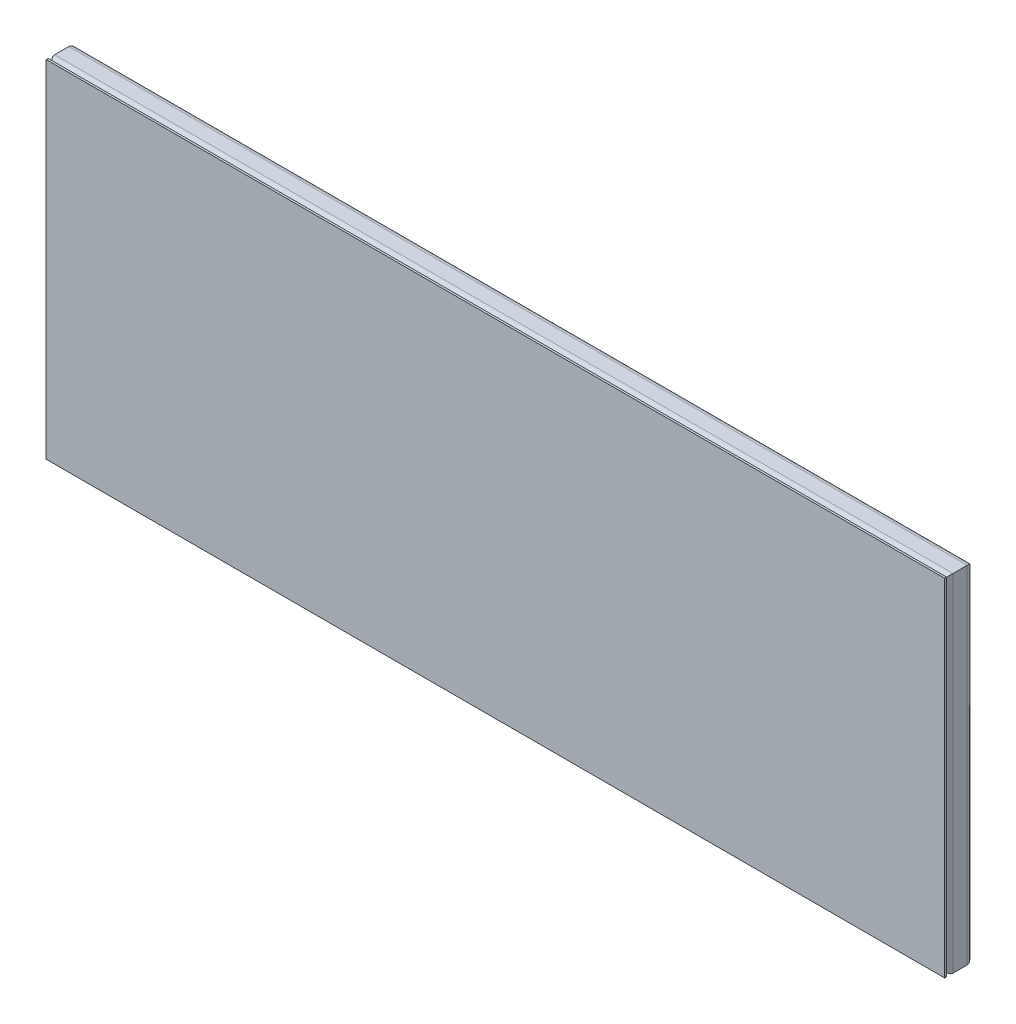
SolidWorks part; units mm, degrees
ref_plane "Alzado" through (0, 0, 0) normal (0, 0, 1) x (1, 0, 0)
ref_plane "Planta" through (0, 0, 0) normal (0, 1, 0) x (1, 0, 0)
ref_plane "Vista lateral" through (0, 0, 0) normal (1, 0, 0) x (0, 0, -1)
sketch "Croquis1" plane through (0, 0, 0) normal (0, 0, 1) x (1, 0, 0)
  line L1 (-400, 138.5) -> (400, 138.5)
  line L2 (-400, 138.5) -> (-400, -138.5)
  line L3 (-400, -138.5) -> (400, -138.5)
  line L4 (400, 138.5) -> (400, -138.5)
  line L5 (-400, 138.5) -> (400, -138.5) construction
  line L6 (-400, -138.5) -> (400, 138.5) construction
  point P0 (0, 0)
  dimension "D1" = 800
  dimension "D2" = 277
other "Tubo cuadrado 2 X 2 X 0.25(1)"
ref_plane "Plano1" through (-412.7, 138.5, 12.7) normal (0, -1, 0) x (1, 0, 0)
sketch "Sketch1" plane through (-412.7, 138.5, 12.7) normal (0, -1, 0) x (1, 0, 0)
  line L0 (-6.7, -9.7) -> (6.7, -9.7)
  line L1 (-9.7, -6.7) -> (-9.7, 6.7)
  line L2 (6.7, 9.7) -> (-6.7, 9.7)
  line L3 (9.7, 6.7) -> (9.7, -6.7)
  line L4 (-6.7, -12.7) -> (6.7, -12.7)
  line L5 (-12.7, -6.7) -> (-12.7, 6.7)
  line L6 (6.7, 12.7) -> (-6.7, 12.7)
  line L7 (12.7, 6.7) -> (12.7, -6.7)
  line L8 (0, 0) -> (9.7, 0) construction
  line L9 (0, 0) -> (0, 9.7) construction
  arc A0 (12.7, 6.7) -> (6.7, 12.7) centre (6.7, 6.7) ccw
  arc A1 (6.7, -12.7) -> (12.7, -6.7) centre (6.7, -6.7) ccw
  arc A2 (-12.7, -6.7) -> (-6.7, -12.7) centre (-6.7, -6.7) ccw
  arc A3 (-6.7, 12.7) -> (-12.7, 6.7) centre (-6.7, 6.7) ccw
  arc A4 (-6.7, 9.7) -> (-9.7, 6.7) centre (-6.7, 6.7) ccw
  arc A5 (9.7, 6.7) -> (6.7, 9.7) centre (6.7, 6.7) ccw
  arc A6 (6.7, -9.7) -> (9.7, -6.7) centre (6.7, -6.7) ccw
  arc A7 (-9.7, -6.7) -> (-6.7, -9.7) centre (-6.7, -6.7) ccw
  point P3 (0, 12.7)
  point P4 (12.7, 0)
  point P5 (0, -12.7)
  point P6 (-12.7, 0)
  point P7 (-12.7, 12.7)
  point P8 (-12.7, -12.7)
  point P33 (0, 0)
  point P35 (12.7, -12.7)
  point P36 (12.7, 12.7)
  point P37 (0, 0)
  dimension "D1" = 6
  dimension "Thickness" = 3
  dimension "V_leg" = 25.4
sketch "Croquis3" plane through (0, 0, 25.4) normal (0, 0, 1) x (1, 0, 0)
  line L1 (-425.4, -163.9) -> (425.4, -163.9)
  line L2 (-425.4, -163.9) -> (-425.4, 163.9)
  line L3 (-425.4, 163.9) -> (425.4, 163.9)
  line L4 (425.4, -163.9) -> (425.4, 163.9)
  line L5 (-425.4, -163.9) -> (425.4, 163.9) construction
  line L6 (-425.4, 163.9) -> (425.4, -163.9) construction
  point P0 (0, 0)
extrude "Saliente-Extruir1" add sketch "Croquis3" along normal blind 1.9 separate body
